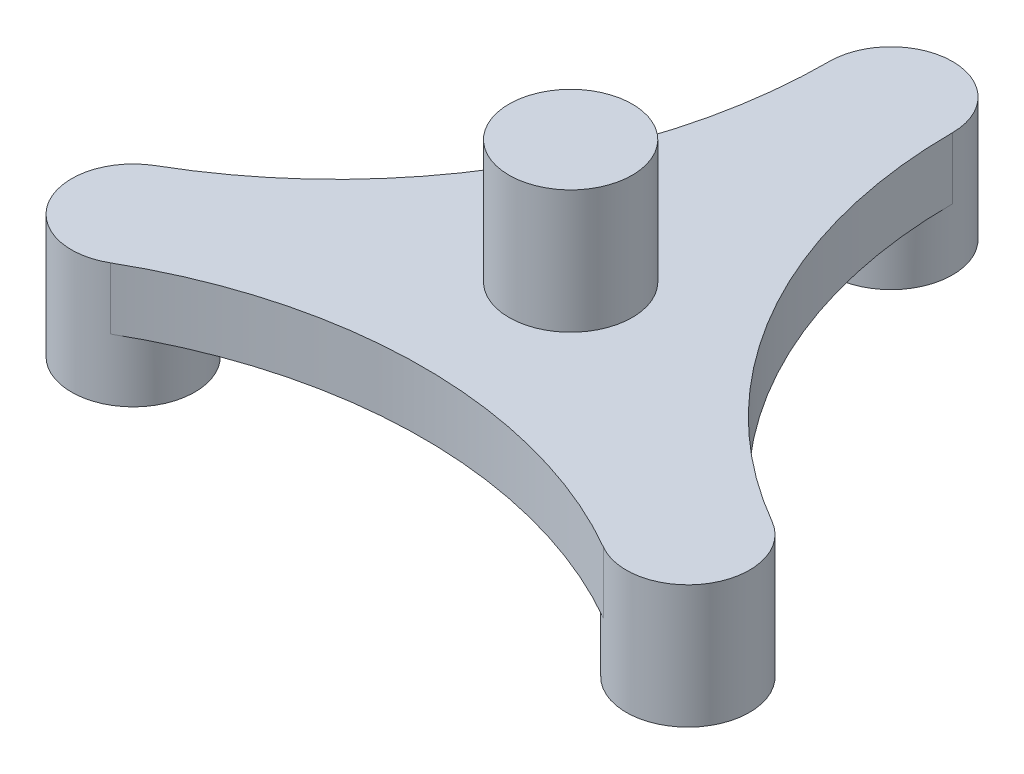
SolidWorks part; units mm, degrees
ref_plane "Front Plane" through (0, 0, 0) normal (0, 0, 1) x (1, 0, 0)
ref_plane "Top Plane" through (0, 0, 0) normal (0, 1, 0) x (1, 0, 0)
ref_plane "Right Plane" through (0, 0, 0) normal (1, 0, 0) x (0, 0, -1)
sketch "Sketch1" plane through (0, 0, 0) normal (0, 1, 0) x (1, 0, 0)
  line L0 (12.7, 65.9911) -> (-12.7, 65.9911) construction
  line L1 (0, 65.9911) -> (-57.15, -32.9956) construction
  line L2 (-57.15, -32.9956) -> (57.15, -32.9956) construction
  line L3 (57.15, -32.9956) -> (0, 65.9911) construction
  line L4 (-50.8, -43.9941) -> (-63.5, -21.997) construction
  line L5 (50.8, -43.9941) -> (63.5, -21.997) construction
  line L6 (-57.15, -32.9956) -> (0, 0) construction
  line L7 (0, 0) -> (0, 65.9911) construction
  line L8 (0, 0) -> (57.15, -32.9956) construction
  circle A0 centre (0, 0) radius 30.1024 construction
  arc A1 (-50.8, -43.9941) -> (-63.5, -21.997) centre (-57.15, -32.9956) cw
  arc A2 (-12.7, 65.9911) -> (12.7, 65.9911) centre (0, 65.9911) cw
  arc A3 (63.5, -21.997) -> (50.8, -43.9941) centre (57.15, -32.9956) cw
  arc A7 (-63.5, -21.997) -> (-12.7, 65.9911) centre (-114.3, 65.9911) ccw
  arc A8 (12.7, 65.9911) -> (63.5, -21.997) centre (114.3, 65.9911) ccw
  arc A9 (50.8, -43.9941) -> (-50.8, -43.9941) centre (0, -131.9823) ccw
  point P8 (0, 65.9911)
  point P12 (-57.15, -32.9956)
  point P15 (57.15, -32.9956)
  point P18 (-34.3995, -19.8605)
  point P19 (-55.3345, -31.9474)
  point P20 (-32.7072, -18.8835)
  point P21 (-52.1389, -30.1024)
  point P22 (-37.6769, -21.7527)
  point P23 (-52.5495, -30.3395)
  point P24 (-48.4869, -27.9939)
  dimension "D1" = 25.4
  dimension "D2" = 114.3
extrude "Boss-Extrude1" add sketch "Sketch1" along normal blind 12.7
sketch "Sketch2" plane through (0, 12.7, 0) normal (0, 1, 0) x (1, 0, 0)
  circle A0 centre (0, 0) radius 12.7
  dimension "D1" = 25.4
extrude "Boss-Extrude2" add sketch "Sketch2" along normal blind 25.4
sketch "Sketch3" plane through (0, 0, 0) normal (0, -1, 0) x (1, 0, 0)
  circle A0 centre (-57.15, 32.9956) radius 12.7
  circle A1 centre (57.15, 32.9956) radius 12.7
  circle A2 centre (0, -65.9911) radius 12.7
extrude "Boss-Extrude3" add sketch "Sketch3" along normal blind 12.7
